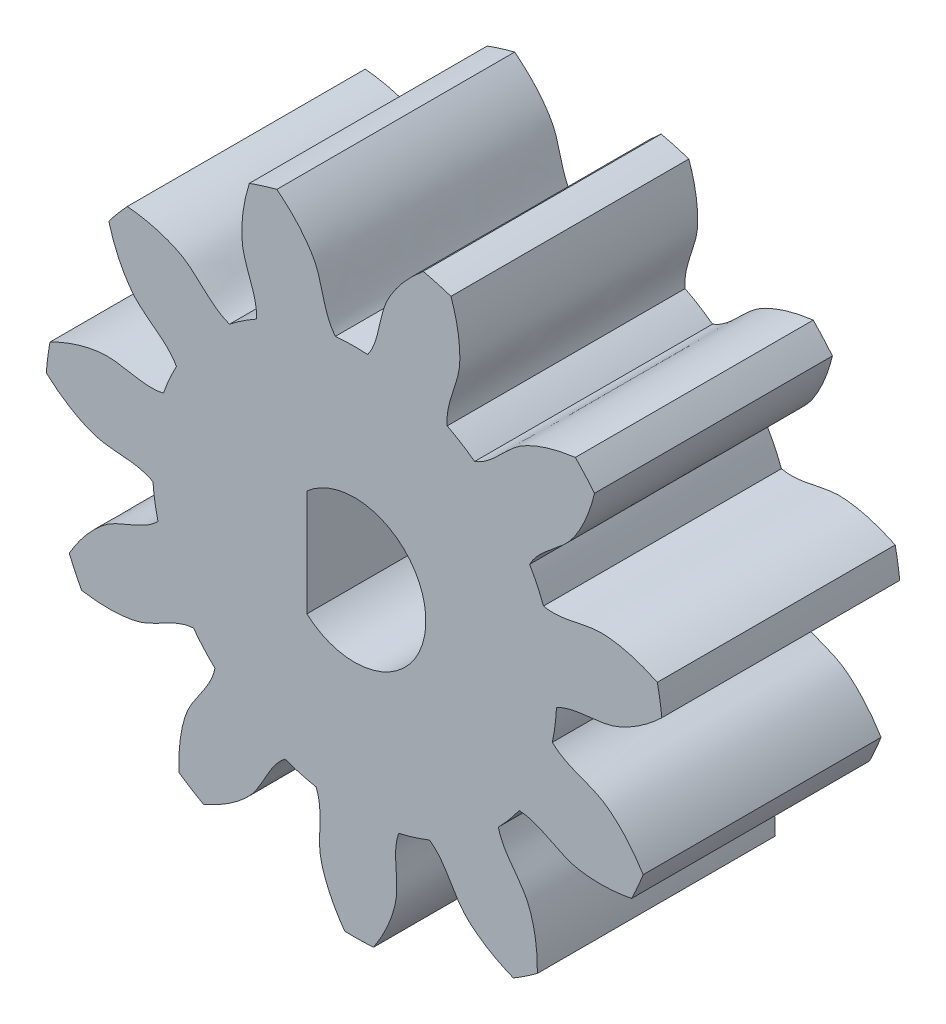
SolidWorks part; units mm, degrees
ref_plane "前视基准面" through (0, 0, 0) normal (0, 0, 1) x (1, 0, 0)
ref_plane "上视基准面" through (0, 0, 0) normal (0, 1, 0) x (1, 0, 0)
ref_plane "右视基准面" through (0, 0, 0) normal (1, 0, 0) x (0, 0, -1)
sketch "草图1" plane through (0, 0, 0) normal (0, 0, 1) x (1, 0, 0)
  line L0 (-1, 1.118) -> (-1, -1.118)
  circle A0 centre (0, 0) radius 4.25
  arc A1 (-1, -1.118) -> (-1, 1.118) centre (0, 0) ccw
  dimension "D1" = 8.5
  dimension "D2" = 3
  dimension "D3" = 1
extrude "凸台-拉伸1" add sketch "草图1" along normal blind 5
sketch "草图2" plane through (0, 0, 0) normal (0, 0, 1) x (1, 0, 0)
  arc A0 (6.3648, 1.3186) -> (6.4599, 0.7208) centre (0, 0) cw
  arc A1 (3.9726, 1.5102) -> (4.2451, -0.2033) centre (0, 0) cw
  spline S0 degree 3 poles (6.4599, 0.7208) (6.305, 0.5734) (6.0602, 0.3729) (5.7051, 0.1679) (5.1522, -0.0796) (4.6061, 0.0047) (4.2451, -0.2033) knots 0 0 0 0 0.262448 0.385242 0.502397 1 1 1 1
  spline S1 degree 3 poles (6.3648, 1.3186) (6.1719, 1.4107) (5.8769, 1.5254) (5.4758, 1.6102) (4.8734, 1.6739) (4.3803, 1.4243) (3.9726, 1.5102) knots 0 0 0 0 0.262448 0.385242 0.502397 1 1 1 1
extrude "凸台-拉伸2" add sketch "草图2" along normal blind 5
pattern_circular "阵列(圆周)1" count 11 over 360 about axis through (0, 0, 5) along (0, 0, -1) of "凸台-拉伸2"
